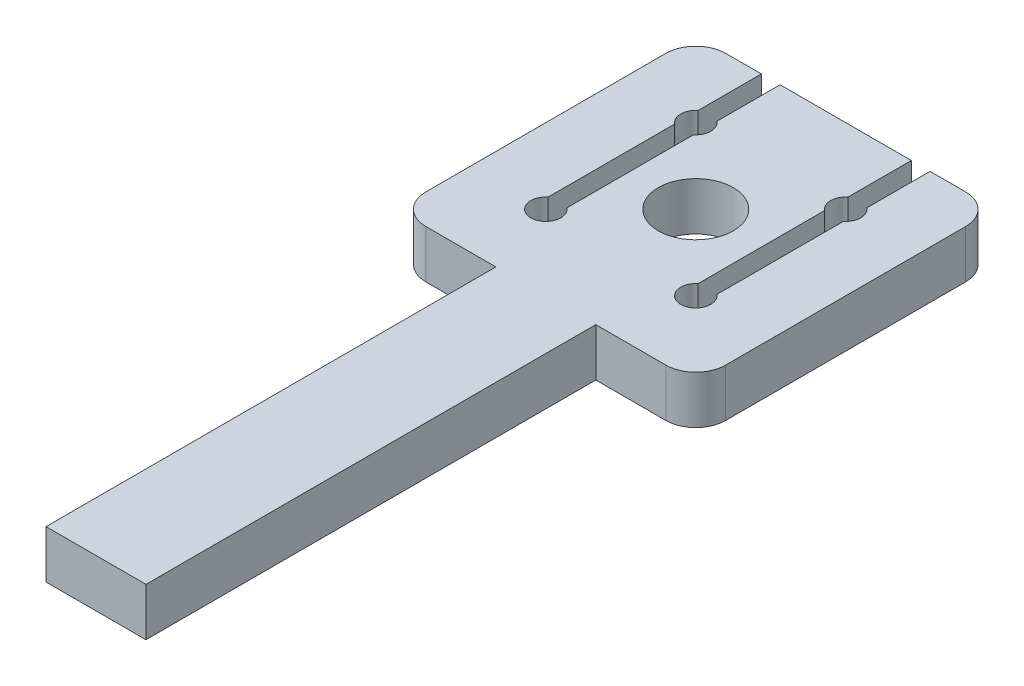
SolidWorks part; units mm, degrees
material "Maple"
ref_plane "Front Plane" through (0, 0, 0) normal (0, 0, 1) x (1, 0, 0)
ref_plane "Top Plane" through (0, 0, 0) normal (0, 1, 0) x (1, 0, 0)
ref_plane "Right Plane" through (0, 0, 0) normal (1, 0, 0) x (0, 0, -1)
sketch "Base_Sketch" plane through (0, 0, 0) normal (0, 1, 0) x (1, 0, 0)
  line L0 (0, -13.6054) -> (0, 17.415) construction
  line L1 (-10, 10) -> (10, 10)
  line L2 (-10, 10) -> (-10, -10)
  line L3 (-10, -10) -> (10, -10) construction
  line L4 (10, 10) -> (10, -10)
  line L5 (-10, 10) -> (10, -10) construction
  line L6 (-10, -10) -> (10, 10) construction
  line L7 (-25.7483, 0) -> (23.2313, 0) construction
  line L8 (5, 5) -> (-5, -5) construction
  line L9 (-10, -10) -> (-3.3333, -10)
  line L10 (-3.3333, -10) -> (-3.3333, -40)
  line L11 (-3.3333, -40) -> (3.3333, -40)
  line L12 (3.3333, -40) -> (3.3333, -10)
  line L13 (3.3333, -10) -> (10, -10)
  line L14 (-5.625, -4.2194) -> (-5.625, 4.2194)
  line L15 (-4.375, -4.2194) -> (-4.375, 4.2194)
  line L16 (-5.625, 5.7806) -> (-5.625, 10)
  line L17 (-4.375, 5.7806) -> (-4.375, 10)
  line L18 (4.375, 5.7806) -> (4.375, 10)
  line L19 (5.625, 5.7806) -> (5.625, 10)
  line L20 (5.625, -4.2194) -> (5.625, 4.2194)
  line L21 (4.375, -4.2194) -> (4.375, 4.2194)
  circle A0 centre (0, 0) radius 2.5
  circle A1 centre (-5, 5) radius 1
  circle A2 centre (5, 5) radius 1
  circle A3 centre (5, -5) radius 1
  circle A4 centre (-5, -5) radius 1
  point P0 (0, 0)
  point P17 (0, 0)
  point P20 (0, 0)
  point P23 (0, 0)
  point P26 (0, 0)
  dimension "D2" = 5
  dimension "D3" = 2
  dimension "D1" = 20
  dimension "D5" = 10
  dimension "D6" = 30
  dimension "1.25" = 1.25
  dimension "D4" = 4
extrude "Boss-Extrude1" add sketch "Base_Sketch" along normal blind 3.2 contours A4 L14 A1 L16 L1 L2 L9 L10 L11 L12 L13 L4 L19 A2 L20 A3 L21 L18 L17 L15 A0
fillet "Fillet1" radius 2 4 edges at (-10, 1.6, -10) (10, 1.6, -10) (-10, 1.6, 10) (10, 1.6, 10)
equation "\"Material_Thickness\"= \"Material_Thickness@Soldering_Jig.Assembly\""
equation "\"D1@Boss-Extrude1\"=\"Material_Thickness\""
